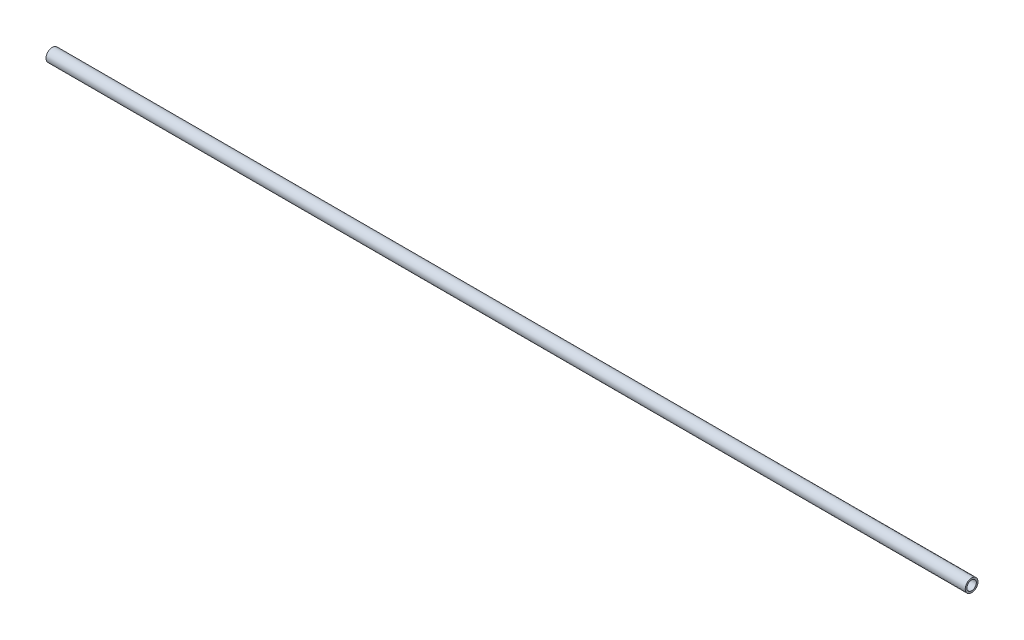
SolidWorks part; units mm, degrees
material "AISI Type 316L stainless steel"
ref_plane "Front" through (0, 0, 0) normal (0, 0, 1) x (1, 0, 0)
ref_plane "Top" through (0, 0, 0) normal (0, 1, 0) x (1, 0, 0)
ref_plane "Right" through (0, 0, 0) normal (1, 0, 0) x (0, 0, -1)
sketch "Sketch1" plane through (0, 0, 0) normal (1, 0, 0) x (0, 0, -1)
  circle A0 centre (0, 0) radius 6.35
  circle A1 centre (0, 0) radius 4.699
  point P4 (6.35, 0)
  point P5 (4.699, 0)
  dimension "OD" = 12.7
  dimension "ID" = 9.398
  dimension "Wall" = 1.651
extrude "Extrude1" add sketch "Sketch1" along normal mid plane 914.4
sketch "Sketch2" plane through (0, 0, 0) normal (0, 0, 1) x (1, 0, 0)
  line L0 (-457.2, 0) -> (457.2, 0) construction
  line L1 (-457.2, 6.35) -> (-457.2, -6.35) construction
